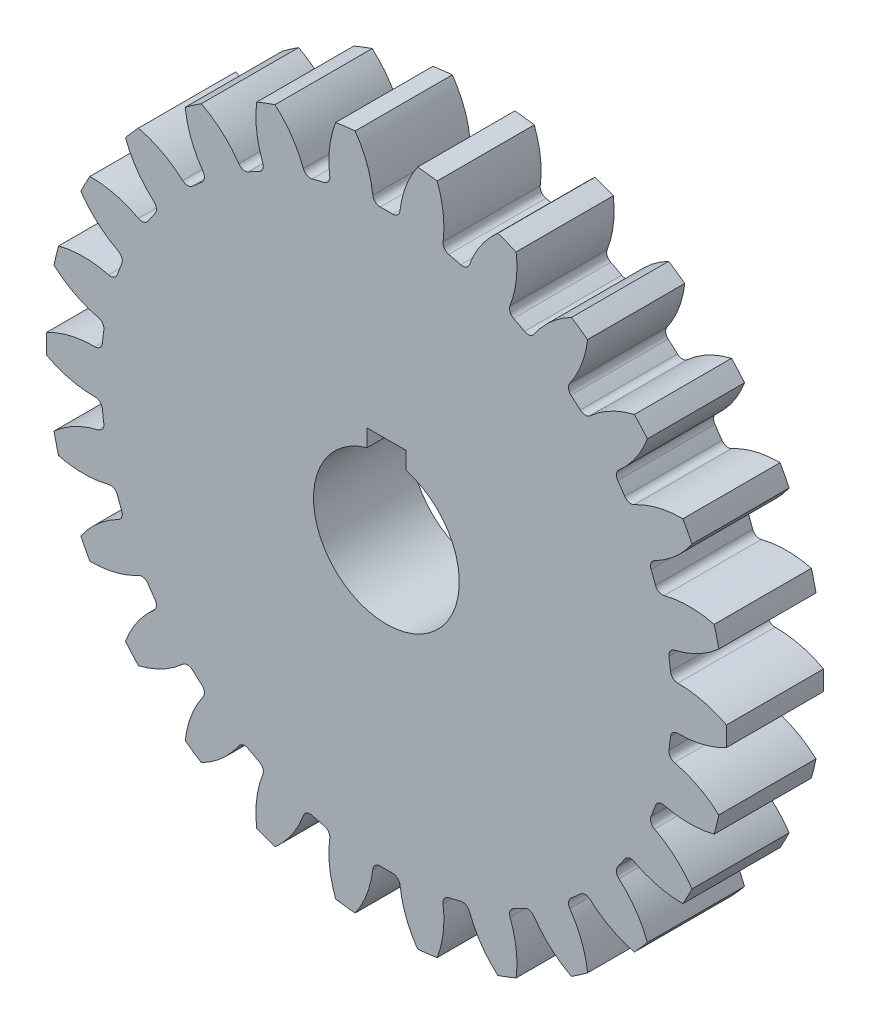
SolidWorks part; units mm, degrees
material "AISI 1035 Steel (SS)"
ref_plane "Front Plane" through (0, 0, 0) normal (0, 0, 1) x (1, 0, 0)
ref_plane "Top Plane" through (0, 0, 0) normal (0, 1, 0) x (1, 0, 0)
ref_plane "Right Plane" through (0, 0, 0) normal (1, 0, 0) x (0, 0, -1)
sketch "Sketch1" plane through (0, 0, 0) normal (0, 0, 1) x (1, 0, 0)
  line L1 (-4, 12) -> (4, 12)
  line L2 (-4, 12) -> (-4, 18)
  line L3 (-4, 18) -> (4, 18)
  line L4 (4, 12) -> (4, 18)
  line L5 (-4, 12) -> (4, 18) construction
  line L6 (-4, 18) -> (4, 12) construction
  circle A0 centre (0, 0) radius 58.75
  circle A1 centre (0, 0) radius 65
  circle A2 centre (0, 0) radius 70
  circle A3 centre (0, 0) radius 15
  circle A4 centre (0, 0) radius 25
  point P6 (0, 15)
  dimension "D1" = 140
  dimension "D2" = 130
  dimension "D4" = 30
  dimension "D7" = 50
  dimension "D3" = 11.25
  dimension "D5" = 6
  dimension "D6" = 8
extrude "Boss-Extrude1" add sketch "Sketch1" along normal blind 20 contours A0 | A1 A0 | A2 A1 | A4 A3 L2 L3 L4
sketch "Sketch2" plane through (0, 0, 0) normal (0, 0, 1) x (1, 0, 0)
  line L0 (0, 0) -> (0, 70) construction
  line L1 (-3.9246, 64.8814) -> (3.9246, 64.8814) construction
  line L2 (0, 0) -> (-2.686, 58.6886) construction
  line L3 (0, 54.0987) -> (-6.0574, 70.7411) construction
  line L4 (0, 0) -> (8.4376, 69.4896) construction
  line L5 (3.9246, 64.8814) -> (11.7166, 63.9353) construction
  circle A0 centre (0, 0) radius 70 construction
  arc A1 (-7.1268, 70.6414) -> (-2.686, 58.6886) centre (-23.5647, 57.733) cw
  arc A2 (7.1268, 70.6414) -> (2.686, 58.6886) centre (23.5647, 57.733) ccw
  circle A3 centre (0, 0) radius 58.75 construction
  arc A4 (2.686, 58.6886) -> (-2.686, 58.6886) centre (0, 0) ccw
  circle A6 centre (0, 0) radius 65 construction
  circle A7 centre (0, 0) radius 71
  arc A8 (7.1268, 70.6414) -> (-7.1268, 70.6414) centre (0, 0) ccw
  dimension "D2" = 20
  dimension "D3" = 6.923
  dimension "D1" = 1
extrude "Cut-Extrude3" cut sketch "Sketch2" along normal through all
fillet "Fillet1" radius 1.5 2 edges at (2.686, 58.6886, 10) (-2.686, 58.6886, 10)
pattern_circular "CirPattern1" count 26 over 360 about axis through (0, 0, 0) along (0, 0, 1) of "Cut-Extrude3", "Fillet1"
equation "\"Module\"= 5"
equation "\"No of Teeth\"= 26"
equation "\"D1@Sketch1\"= (\"No of Teeth\" + 2) * \"Module\""
equation "\"D2@Sketch1\"= \"No of Teeth\" * \"Module\""
equation "\"D3@Sketch1\"=\"Module\" * if ( \"Module\" =>1.25, 2.25, 2.4)"
equation "\"D3@Sketch2\"= 180 / \"No of Teeth\""
equation "\"D1@Fillet1\"= 0.3 * \"Module\""
equation "\"D1@CirPattern1\"= \"No of Teeth\""
equation "\"Face Width\"= 20"
equation "\"Key Hight\"= 6"
equation "\"Key Width\"= 8"
equation "\"Hub Diameter\"= 50"
equation "\"Hub Width\"= 20"
equation "\"D5@Sketch1\"=\"Key Hight\""
equation "\"D6@Sketch1\"=\"Key Width\""
equation "\"Shft Diameter\"= 30"
equation "\"D4@Sketch1\"=\"Shft Diameter\""
equation "\"D1@Boss-Extrude1\"=\"Face Width\""
equation "\"D7@Sketch1\"=\"Hub Diameter\""
equation "\"D1@Boss-Extrude2\"=\"Hub Width\""
equation "\"m\"=10"
